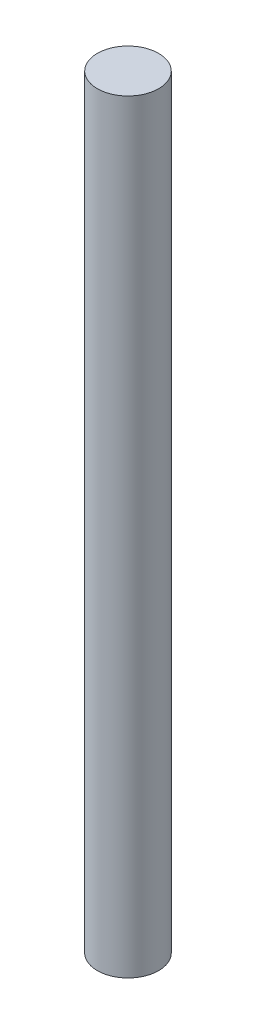
SolidWorks part; units mm, degrees
ref_plane "Front Plane" through (0, 0, 0) normal (0, 0, 1) x (1, 0, 0)
ref_plane "Top Plane" through (0, 0, 0) normal (0, 1, 0) x (1, 0, 0)
ref_plane "Right Plane" through (0, 0, 0) normal (1, 0, 0) x (0, 0, -1)
sketch "Sketch2" plane through (0, 0, 0) normal (0, 1, 0) x (1, 0, 0)
  circle A0 centre (0, 0) radius 1.985
  dimension "D1" = 3.97
extrude "Boss-Extrude1" add sketch "Sketch2" along normal blind 49.5
